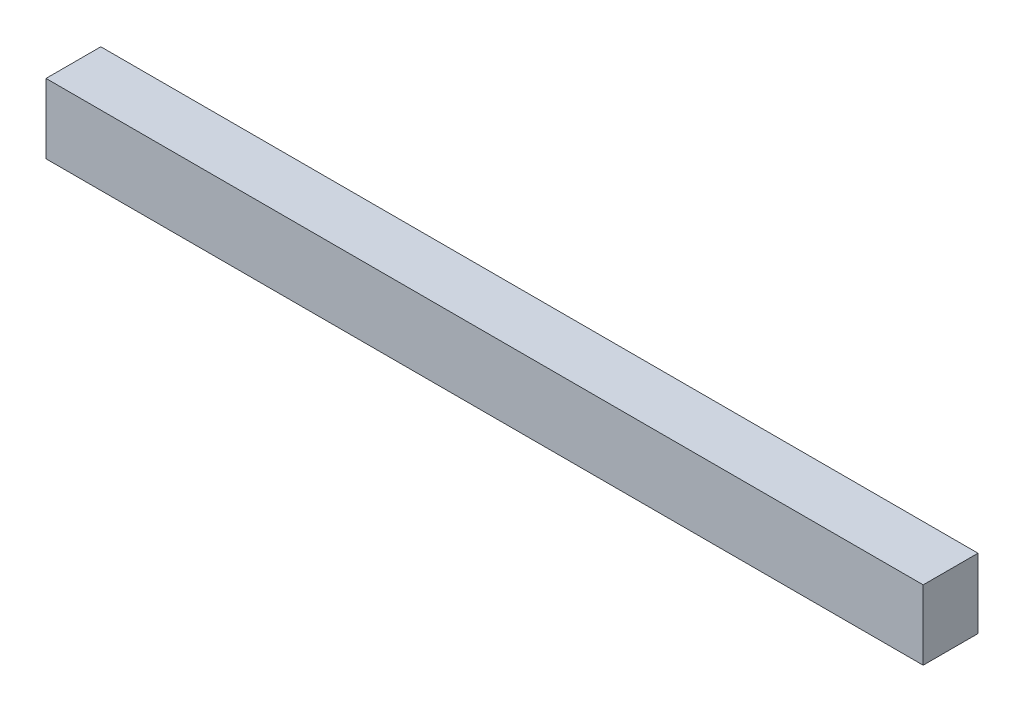
SolidWorks part; units mm, degrees
material "Maple"
ref_plane "Front Plane" through (0, 0, 0) normal (0, 0, 1) x (1, 0, 0)
ref_plane "Top Plane" through (0, 0, 0) normal (0, 1, 0) x (1, 0, 0)
ref_plane "Right Plane" through (0, 0, 0) normal (1, 0, 0) x (0, 0, -1)
sketch "Sketch1" plane through (0, 0, 0) normal (0, 1, 0) x (1, 0, 0)
  line L1 (40, 2.5) -> (-40, 2.5)
  line L2 (40, 2.5) -> (40, -2.5)
  line L3 (40, -2.5) -> (-40, -2.5)
  line L4 (-40, 2.5) -> (-40, -2.5)
  line L5 (40, 2.5) -> (-40, -2.5) construction
  line L6 (40, -2.5) -> (-40, 2.5) construction
  point P0 (0, 0)
  dimension "D1" = 80
  dimension "D2" = 5
extrude "Boss-Extrude1" add sketch "Sketch1" along normal blind 6.35
